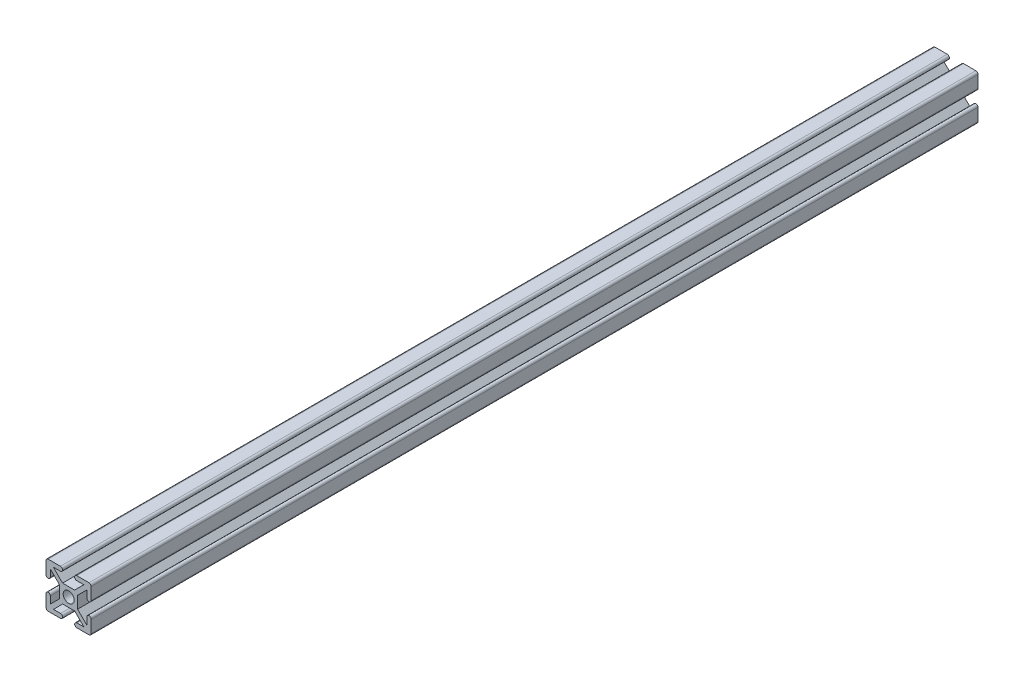
SolidWorks part; units mm, degrees
ref_plane "Alzado" through (0, 0, 0) normal (0, 0, 1) x (1, 0, 0)
ref_plane "Planta" through (0, 0, 0) normal (0, 1, 0) x (1, 0, 0)
ref_plane "Vista lateral" through (0, 0, 0) normal (1, 0, 0) x (0, 0, -1)
sketch "Croquis1" plane through (0, 0, 0) normal (0, 0, 1) x (1, 0, 0)
  line L0 (-33.5182, 2.4579) -> (-33.5182, 3.8829) construction
  line L1 (-14.4653, -13.6921) -> (-9.7403, -13.6921)
  line L2 (-34.9432, 12.0328) -> (-34.9432, 3.8829)
  line L3 (-33.5182, 13.4578) -> (-25.3682, 13.4578)
  line L4 (-14.5182, 13.4578) -> (-6.3682, 13.4578)
  line L5 (-30.0403, -13.6921) -> (-25.3153, -13.6921)
  line L6 (-25.9432, 2.4579) -> (-25.9432, -5.5421)
  line L7 (-34.8903, -6.9671) -> (-34.8903, -15.1171)
  line L8 (-33.4918, -16.5157) -> (-25.3153, -16.5421)
  line L9 (-4.9432, 12.0328) -> (-4.9432, 3.9866)
  line L10 (-32.0932, 8.6079) -> (-32.0932, 3.8829)
  line L11 (-4.9432, -6.8634) -> (-4.9432, -15.1171)
  line L12 (-23.9432, 12.0328) -> (-25.3682, 12.0328) construction
  line L13 (-14.4653, -16.5421) -> (-6.3682, -16.5421)
  line L14 (-30.0932, 10.6078) -> (-25.3682, 10.6078)
  line L15 (-32.0932, -6.9671) -> (-32.0932, -11.6921)
  line L16 (-15.9432, 12.0328) -> (-14.5182, 12.0328) construction
  line L17 (-14.5182, 10.6078) -> (-9.7932, 10.6078)
  line L18 (-6.3682, 2.5616) -> (-6.3682, 3.9866) construction
  line L19 (-23.9432, 4.4578) -> (-30.0932, 10.6078)
  line L20 (-7.7932, 8.6078) -> (-7.7932, 3.9866)
  line L21 (-6.3682, -5.4384) -> (-6.3682, -6.8634) construction
  line L22 (-25.9432, 2.4579) -> (-32.0932, 8.6079)
  line L23 (-7.7932, -6.8634) -> (-7.7932, -11.6922)
  line L24 (-15.8903, -15.1171) -> (-14.4653, -15.1171) construction
  line L25 (-25.9432, -5.5421) -> (-32.0932, -11.6921)
  line L26 (-23.9432, 4.4578) -> (-15.9432, 4.4578)
  line L27 (-15.9432, 4.4578) -> (-9.7932, 10.6078)
  line L28 (-33.4918, -5.5421) -> (-33.4918, -6.9671) construction
  line L29 (-30.0403, -13.6921) -> (-23.8903, -7.5421)
  line L30 (-23.8903, -7.5421) -> (-15.8903, -7.5421)
  line L31 (-15.8903, -7.5421) -> (-9.7403, -13.6921)
  line L32 (-23.8903, -15.1171) -> (-25.3153, -15.1171) construction
  line L33 (-13.9432, -5.5422) -> (-7.7932, -11.6922)
  line L34 (-13.9432, 2.4578) -> (-7.7932, 8.6078)
  line L35 (-13.9432, 2.4578) -> (-13.9432, -5.5422)
  circle A0 centre (-19.8903, -1.5421) radius 3.645
  arc A1 (-34.9432, 3.8829) -> (-32.0932, 3.8829) centre (-33.5182, 3.8829) ccw
  arc A2 (-25.3682, 10.6078) -> (-25.3682, 13.4578) centre (-25.3682, 12.0328) ccw
  arc A3 (-14.5182, 13.4578) -> (-14.5182, 10.6078) centre (-14.5182, 12.0328) ccw
  arc A4 (-7.7932, 3.9866) -> (-4.9432, 3.9866) centre (-6.3682, 3.9866) ccw
  arc A5 (-4.9432, -6.8634) -> (-7.7932, -6.8634) centre (-6.3682, -6.8634) ccw
  arc A6 (-14.4653, -13.6921) -> (-14.4653, -16.5421) centre (-14.4653, -15.1171) ccw
  arc A7 (-32.0932, -6.9671) -> (-34.8903, -6.9671) centre (-33.4918, -6.9671) ccw
  arc A8 (-25.3153, -16.5421) -> (-25.3153, -13.6921) centre (-25.3153, -15.1171) ccw
  arc A9 (-34.8903, -15.1171) -> (-33.4918, -16.5157) centre (-33.4918, -15.1171) ccw
  arc A10 (-6.3682, -16.5421) -> (-4.9432, -15.1171) centre (-6.3682, -15.1171) ccw
  arc A11 (-4.9432, 12.0328) -> (-6.3682, 13.4578) centre (-6.3682, 12.0328) ccw
  arc A12 (-33.5182, 13.4578) -> (-34.9432, 12.0328) centre (-33.5182, 12.0328) ccw
  dimension "D1" = 7.29
  dimension "D2" = 1.425
  dimension "D3" = 1.425
  dimension "D4" = 1.425
  dimension "D5" = 1.425
  dimension "D6" = 1.425
  dimension "D7" = 1.425
  dimension "D8" = 1.425
  dimension "D9" = 1.425
extrude "Saliente-Extruir1" add sketch "Croquis1" along normal blind 589.32
